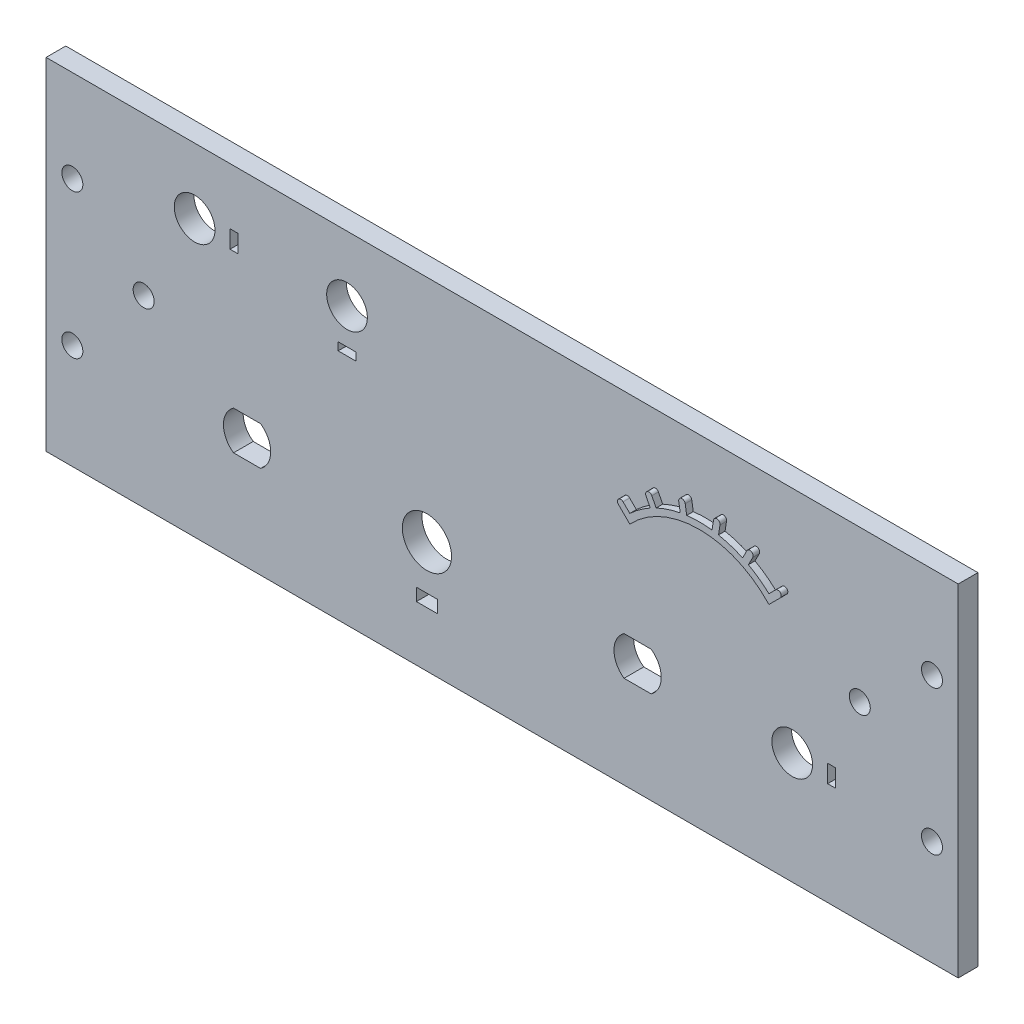
SolidWorks part; units mm, degrees
ref_plane "Front Plane" through (0, 0, 0) normal (0, 0, 1) x (1, 0, 0)
ref_plane "Top Plane" through (0, 0, 0) normal (0, 1, 0) x (1, 0, 0)
ref_plane "Right Plane" through (0, 0, 0) normal (1, 0, 0) x (0, 0, -1)
sketch "Sketch1" plane through (0, 0, 0) normal (0, 0, 1) x (1, 0, 0)
  line L0 (56.432, 8.3939) -> (59.632, 8.3939)
  line L1 (0, 0) -> (139, 0)
  line L2 (0, 0) -> (0, 52)
  line L3 (0, 52) -> (139, 52)
  line L4 (139, 0) -> (139, 52)
  line L5 (69.5, 52) -> (69.5, 0) construction
  line L17 (22.6344, 42.0476) -> (33.4387, 42.0476) construction
  line L20 (29.2344, 40.6976) -> (29.2344, 43.3976)
  line L27 (29.2344, 40.6976) -> (28.0344, 40.6976)
  line L28 (28.0344, 40.6976) -> (28.0344, 43.3976)
  line L29 (29.2344, 43.3976) -> (28.0344, 43.3976)
  line L30 (29.2344, 40.6976) -> (28.0344, 43.3976) construction
  line L31 (28.0344, 40.6976) -> (29.2344, 43.3976) construction
  line L45 (88.0761, 14.0939) -> (92.2029, 14.0939)
  line L52 (92.2029, 19.9939) -> (88.0761, 19.9939)
  line L53 (45.8575, 42.1214) -> (45.8575, 36.1214) construction
  line L54 (44.5075, 35.5214) -> (47.2075, 35.5214)
  line L59 (44.5075, 35.5214) -> (44.5075, 36.7214)
  line L60 (44.5075, 36.7214) -> (47.2075, 36.7214)
  line L61 (47.2075, 35.5214) -> (47.2075, 36.7214)
  line L66 (44.5075, 35.5214) -> (47.2075, 36.7214) construction
  line L67 (44.5075, 36.7214) -> (47.2075, 35.5214) construction
  line L68 (113.7029, 17.0439) -> (108.3199, 17.0439) construction
  line L69 (56.432, 8.3939) -> (56.432, 10.2939)
  line L70 (56.432, 10.2939) -> (59.632, 10.2939)
  line L71 (59.632, 8.3939) -> (59.632, 10.2939)
  line L72 (56.432, 8.3939) -> (59.632, 10.2939) construction
  line L73 (56.432, 10.2939) -> (59.632, 8.3939) construction
  line L74 (28.565, 14.0939) -> (32.6917, 14.0939)
  line L75 (32.6917, 19.9939) -> (28.565, 19.9939)
  line L76 (120.3029, 15.6939) -> (120.3029, 18.3939)
  line L77 (120.3029, 15.6939) -> (119.1029, 15.6939)
  line L78 (119.1029, 15.6939) -> (119.1029, 18.3939)
  line L79 (120.3029, 18.3939) -> (119.1029, 18.3939)
  line L80 (120.3029, 15.6939) -> (119.1029, 18.3939) construction
  line L81 (119.1029, 15.6939) -> (120.3029, 18.3939) construction
  circle A0 centre (22.6344, 42.0476) radius 3.1
  circle A4 centre (4, 38) radius 1.6
  circle A5 centre (135, 38) radius 1.6
  circle A6 centre (135, 16) radius 1.6
  circle A7 centre (4, 16) radius 1.6
  circle A9 centre (14.8661, 28) radius 1.6
  circle A11 centre (124, 28.9229) radius 1.6
  circle A17 centre (58.032, 17.0439) radius 3.75
  arc A19 (28.565, 19.9939) -> (28.565, 14.0939) centre (30.6284, 17.0439) ccw
  arc A20 (32.6917, 14.0939) -> (32.6917, 19.9939) centre (30.6284, 17.0439) ccw
  circle A21 centre (30.6284, 17.0439) radius 3.6 construction
  arc A22 (88.0761, 19.9939) -> (88.0761, 14.0939) centre (90.1395, 17.0439) ccw
  arc A23 (92.2029, 14.0939) -> (92.2029, 19.9939) centre (90.1395, 17.0439) ccw
  circle A24 centre (90.1395, 17.0439) radius 3.6 construction
  circle A25 centre (45.8575, 42.1214) radius 3.1
  circle A26 centre (113.7029, 17.0439) radius 3.1
  point P8 (0, 26)
  point P14 (58.032, 9.3439)
  point P36 (28.6344, 42.0476)
  point P45 (45.8575, 36.1214)
  point P58 (119.7029, 17.0439)
  dimension "D3" = 6.2
  dimension "D4" = 7.5
  dimension "D5" = 3.2
  dimension "D8" = 3.2
  dimension "D24" = 7.7
  dimension "D25" = 28
  dimension "D29" = 7.2
  dimension "D19" = 3.2
  dimension "D31" = 6.2
  dimension "D34" = 6
  dimension "D6" = 1.9
  dimension "D32" = 2.7
  dimension "D16" = 7.2
  dimension "D21" = 6.2
  dimension "D1" = 139
  dimension "D2" = 52
  dimension "D7" = 5.9
  dimension "D11" = 131
  dimension "D12" = 4
  dimension "D13" = 14
  dimension "D14" = 22
  dimension "D15" = 16
  dimension "D17" = 15
  dimension "D18" = 15
  dimension "D20" = 4
  dimension "D22" = 2.7
  dimension "D23" = 1.2
  dimension "D26" = 2.7
  dimension "D27" = 1.2
  dimension "D28" = 6
  dimension "D30" = 6
  dimension "D33" = 1.2
  dimension "D35" = 5.9
  dimension "D9" = 2
  dimension "D10" = 2
extrude "Boss-Extrude1" add sketch "Sketch1" along normal blind 3
sketch "Sketch2" plane through (0, 0, 3) normal (0, 0, 1) x (1, 0, 0)
  line L0 (100.5523, 25.9817) -> (93.7424, 39.3468) construction
  line L1 (100.5523, 25.9817) -> (89.9457, 36.5883) construction
  line L2 (100.5523, 25.9817) -> (98.2058, 40.797) construction
  line L3 (100.5523, 25.9817) -> (102.8988, 40.797) construction
  line L4 (100.5523, 25.9817) -> (107.3621, 39.3468) construction
  line L5 (100.5523, 25.9817) -> (111.1589, 36.5883) construction
  line L6 (111.1589, 36.5883) -> (112.5311, 37.9605) construction
  line L7 (107.3621, 39.3468) -> (108.2432, 41.0759) construction
  line L8 (102.8988, 40.797) -> (103.2024, 42.7137) construction
  line L9 (98.2058, 40.797) -> (97.9022, 42.7137) construction
  line L10 (93.7424, 39.3468) -> (92.8614, 41.0759) construction
  line L11 (89.9457, 36.5883) -> (88.5735, 37.9605) construction
  line L12 (111.1532, 37.2897) -> (112.1776, 38.3141)
  line L13 (89.9514, 37.2897) -> (88.927, 38.3141)
  line L14 (108.031, 39.5581) -> (108.6887, 40.8489)
  line L15 (103.4696, 41.2047) -> (103.6962, 42.6355)
  line L16 (98.6227, 41.3611) -> (98.396, 42.792)
  line L17 (93.9646, 40.0121) -> (93.3069, 41.3029)
  line L18 (111.1528, 35.8751) -> (112.8847, 37.607)
  line L19 (89.9518, 35.8751) -> (88.2199, 37.607)
  line L20 (107.14, 40.0121) -> (107.7977, 41.3029)
  line L21 (102.4819, 41.3611) -> (102.7085, 42.792)
  line L22 (97.635, 41.2047) -> (97.4083, 42.6355)
  line L23 (93.0736, 39.5581) -> (92.4159, 40.8489)
  line L24 (93.2969, 39.1198) -> (92.4159, 40.8489) construction
  line L25 (94.1879, 39.5738) -> (93.3069, 41.3029) construction
  line L26 (97.7119, 40.7188) -> (97.4083, 42.6355) construction
  line L27 (98.6996, 40.8752) -> (98.396, 42.792) construction
  line L28 (102.405, 40.8752) -> (102.7085, 42.792) construction
  line L29 (103.3926, 40.7188) -> (103.6962, 42.6355) construction
  line L30 (106.9166, 39.5738) -> (107.7977, 41.3029) construction
  line L31 (107.8076, 39.1198) -> (108.6887, 40.8489) construction
  arc A0 (111.1589, 36.5883) -> (89.9457, 36.5883) centre (100.5523, 25.9817) ccw construction
  arc A1 (111.1532, 37.2897) -> (108.031, 39.5581) centre (100.5523, 25.9817) ccw
  arc A2 (111.1528, 35.8751) -> (89.9518, 35.8751) centre (100.5523, 25.9817) ccw
  arc A3 (112.1776, 38.3141) -> (112.8847, 37.607) centre (112.5311, 37.9605) cw
  arc A4 (88.927, 38.3141) -> (88.2199, 37.607) centre (88.5735, 37.9605) ccw
  arc A5 (107.8076, 39.1198) -> (107.8038, 39.1124) centre (107.3621, 39.3468) cw
  arc A6 (108.6887, 40.8489) -> (107.7977, 41.3029) centre (108.2432, 41.0759) ccw
  arc A7 (103.3926, 40.7188) -> (103.3913, 40.7106) centre (102.8988, 40.797) cw
  arc A8 (103.6962, 42.6355) -> (102.7085, 42.792) centre (103.2024, 42.7137) ccw
  arc A9 (98.6996, 40.8752) -> (98.7008, 40.867) centre (98.2058, 40.797) cw
  arc A10 (98.396, 42.792) -> (97.4083, 42.6355) centre (97.9022, 42.7137) ccw
  arc A11 (94.1879, 39.5738) -> (94.1917, 39.5663) centre (93.7424, 39.3468) cw
  arc A12 (93.3069, 41.3029) -> (92.4159, 40.8489) centre (92.8614, 41.0759) ccw
  arc A13 (93.3008, 39.1124) -> (93.2969, 39.1198) centre (93.7424, 39.3468) cw
  arc A14 (93.0736, 39.5581) -> (89.9514, 37.2897) centre (100.5523, 25.9817) ccw
  arc A15 (111.1532, 37.2897) -> (89.9514, 37.2897) centre (100.5523, 25.9817) ccw construction
  arc A16 (97.635, 41.2047) -> (93.9646, 40.0121) centre (100.5523, 25.9817) ccw
  arc A17 (97.7133, 40.7106) -> (97.7119, 40.7188) centre (98.2058, 40.797) cw
  arc A18 (102.4819, 41.3611) -> (98.6227, 41.3611) centre (100.5523, 25.9817) ccw
  arc A19 (102.4037, 40.867) -> (102.405, 40.8752) centre (102.8988, 40.797) cw
  arc A20 (107.14, 40.0121) -> (103.4696, 41.2047) centre (100.5523, 25.9817) ccw
  arc A21 (106.9129, 39.5663) -> (106.9166, 39.5738) centre (107.3621, 39.3468) cw
  dimension "D1" = 15
  dimension "D2" = 6
  dimension "D3" = 6
  dimension "D4" = 0.5
  dimension "D5" = 0.5
extrude "Boss-Extrude2" add sketch "Sketch2" along normal blind 1
